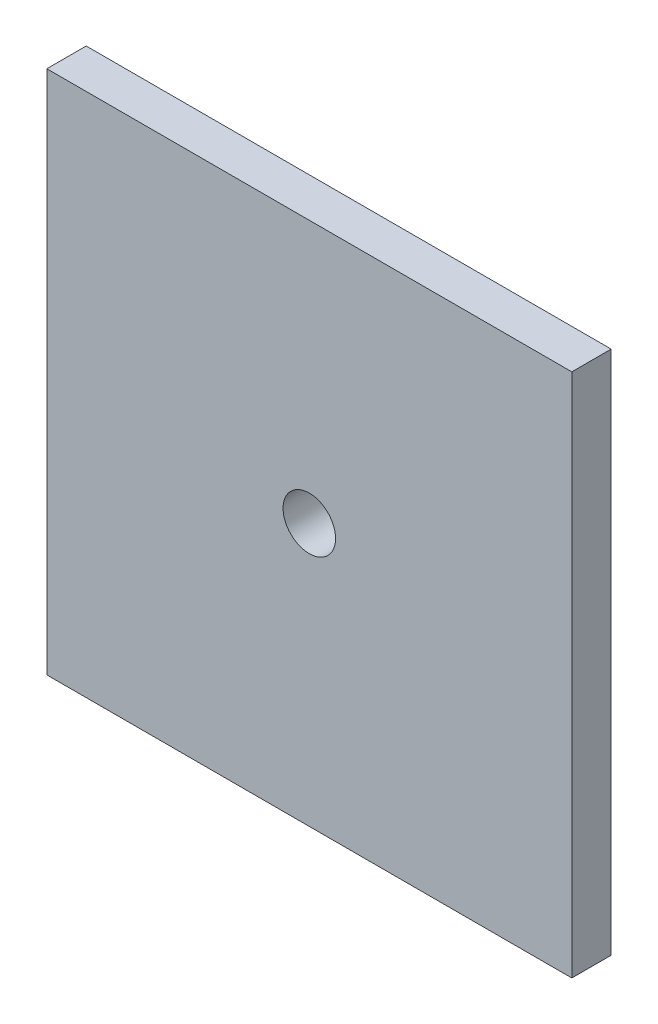
SolidWorks part; units mm, degrees
ref_plane "正面" through (0, 0, 0) normal (0, 0, 1) x (1, 0, 0)
ref_plane "平面" through (0, 0, 0) normal (0, 1, 0) x (1, 0, 0)
ref_plane "右側面" through (0, 0, 0) normal (1, 0, 0) x (0, 0, -1)
sketch "Sketch1" plane through (0, 0, 0) normal (0, 0, 1) x (1, 0, 0)
  line L1 (-40, 40) -> (40, 40)
  line L2 (-40, 40) -> (-40, -40)
  line L3 (-40, -40) -> (40, -40)
  line L4 (40, 40) -> (40, -40)
  line L5 (-40, 40) -> (40, -40) construction
  line L6 (-40, -40) -> (40, 40) construction
  point P0 (0, 0)
  dimension "D1" = 80
  dimension "D2" = 80
extrude "Boss-Extrude1" add sketch "Sketch1" along normal blind 6
sketch "Sketch2" plane through (0, 0, 6) normal (0, 0, 1) x (1, 0, 0)
  circle A0 centre (0, 0) radius 4
  dimension "D1" = 8
extrude "Cut-Extrude1" cut sketch "Sketch2" against normal blind 6
